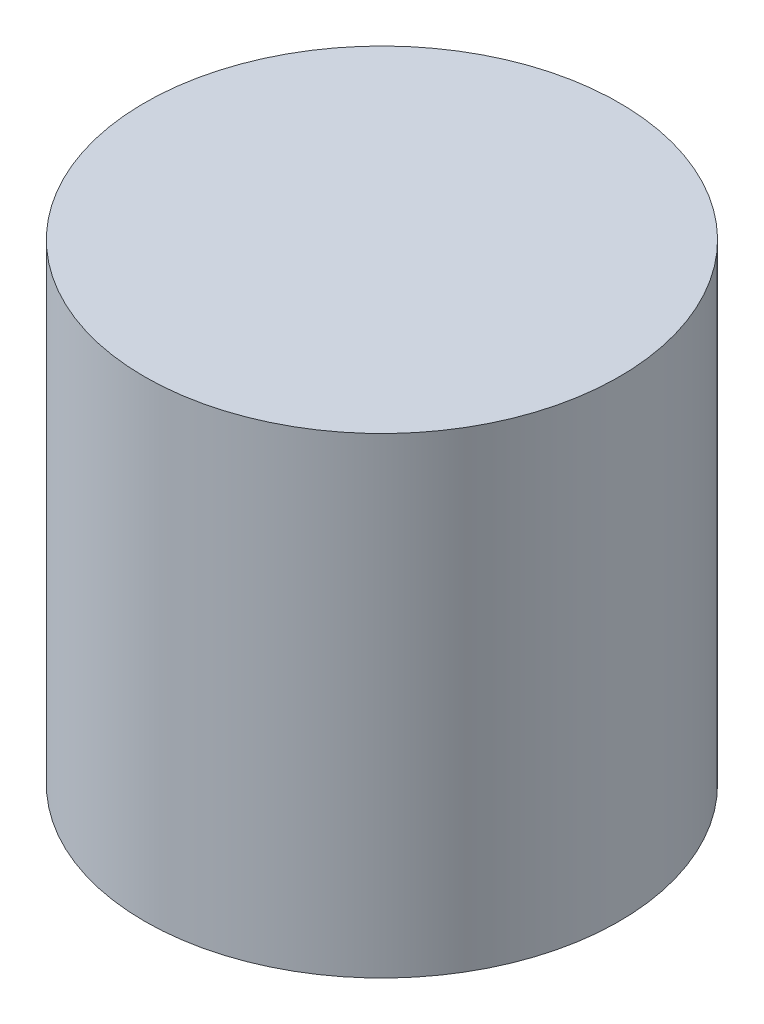
SolidWorks part; units mm, degrees
ref_plane "Front Plane" through (0, 0, 0) normal (0, 0, 1) x (1, 0, 0)
ref_plane "Top Plane" through (0, 0, 0) normal (0, 1, 0) x (1, 0, 0)
ref_plane "Right Plane" through (0, 0, 0) normal (1, 0, 0) x (0, 0, -1)
sketch "Sketch1" plane through (0, 0, 0) normal (0, 1, 0) x (1, 0, 0)
  circle A0 centre (0, 0) radius 3.937
  dimension "D1" = 7.874
extrude "Boss-Extrude1" add sketch "Sketch1" along normal blind 7.8232
